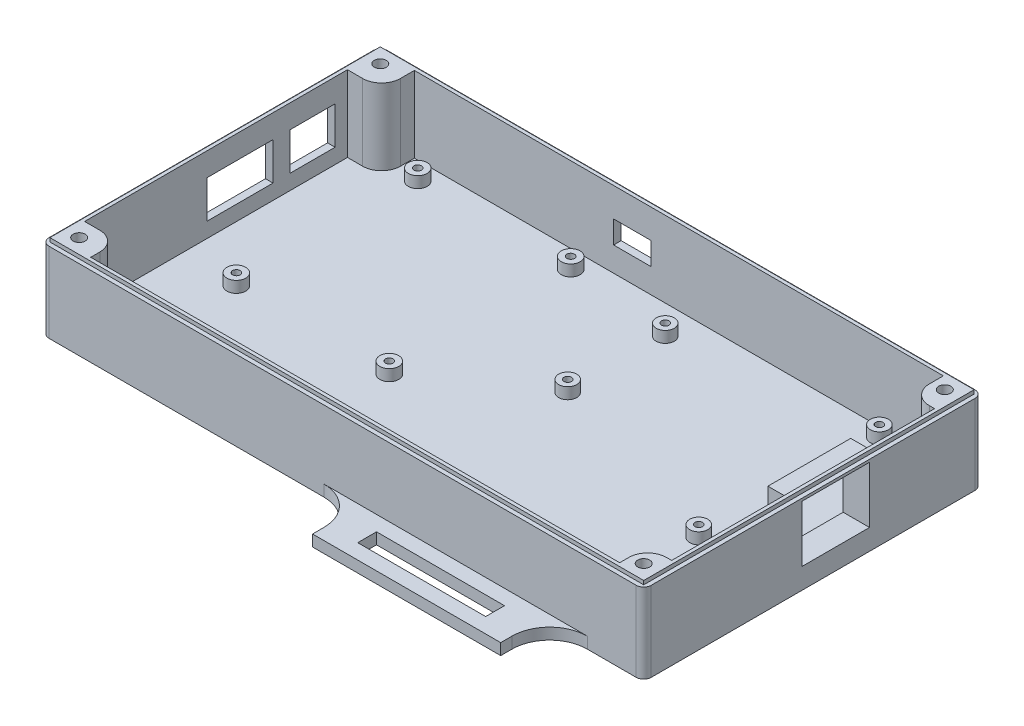
SolidWorks part; units mm, degrees
ref_plane "Front Plane" through (0, 0, 0) normal (0, 0, 1) x (1, 0, 0)
ref_plane "Top Plane" through (0, 0, 0) normal (0, 1, 0) x (1, 0, 0)
ref_plane "Right Plane" through (0, 0, 0) normal (1, 0, 0) x (0, 0, -1)
sketch "Sketch1" plane through (0, 0, 0) normal (0, 1, 0) x (1, 0, 0)
  line L1 (0, 0) -> (160, 0)
  line L2 (0, 0) -> (0, 90)
  line L3 (0, 90) -> (160, 90)
  line L4 (160, 0) -> (160, 90)
  dimension "D1" = 90
  dimension "D2" = 160
extrude "Boss-Extrude1" add sketch "Sketch1" along normal blind 22.2
shell "Shell1" thickness 2
sketch "Sketch2" plane through (0, 2, 0) normal (0, 1, 0) x (1, 0, 0)
  line L0 (2, 2) -> (158, 2) construction
  line L1 (158, 88) -> (2, 88) construction
  line L2 (2, 9.4298) -> (11.0517, 9.4298)
  line L3 (2, 9.4298) -> (2, 2)
  line L4 (2, 2) -> (158, 2) construction
  line L5 (2, 2) -> (11.0517, 2)
  line L6 (11.0517, 9.4298) -> (11.0517, 2)
  line L7 (2, 88) -> (2, 2) construction
  line L8 (151.6221, 79.2822) -> (158, 79.2822)
  line L9 (158, 88) -> (158, 79.2822)
  line L10 (151.6221, 2) -> (158, 2)
  line L11 (151.6221, 79.2822) -> (151.6221, 88)
  line L12 (158, 88) -> (151.6221, 88)
  line L13 (151.6221, 9.4298) -> (151.6221, 2)
  line L14 (158, 2) -> (158, 88) construction
  line L15 (151.6221, 9.4298) -> (158, 9.4298)
  line L16 (158, 9.4298) -> (158, 2)
  line L23 (2, 88) -> (11.0517, 88)
  line L24 (2, 88) -> (2, 79.2822)
  line L25 (2, 79.2822) -> (11.0517, 79.2822)
  line L26 (11.0517, 88) -> (11.0517, 79.2822)
  dimension "D1" = 6.3779
extrude "Boss-Extrude2" add sketch "Sketch2" along normal up to surface (20.2 mm away) up to face at (80, 22.2, -45)
sketch "Sketch5" plane through (0, 22.2, 0) normal (0, 1, 0) x (1, 0, 0)
  line L1 (160, 90) -> (0, 90)
  line L2 (160, 90) -> (160, 0)
  line L3 (160, 0) -> (0, 0)
  line L4 (0, 90) -> (0, 0)
  line L5 (1.1, 1.1) -> (158.9, 1.1)
  line L6 (1.1, 1.1) -> (1.1, 88.9)
  line L7 (1.1, 88.9) -> (158.9, 88.9)
  line L8 (158.9, 1.1) -> (158.9, 88.9)
  dimension "D1" = 1.1
  dimension "D2" = 1.1
  dimension "D3" = 1.1
  dimension "D4" = 1.1
extrude "Cut-Extrude2" cut sketch "Sketch5" against normal blind 1
sketch "Sketch6" plane through (0, 22.2, 0) normal (0, 1, 0) x (1, 0, 0)
  line L0 (160, 0) -> (160, 90) construction
  line L1 (0, 0) -> (160, 0) construction
  line L3 (160, 90) -> (0, 90) construction
  line L5 (0, 90) -> (0, 0) construction
  line L7 (0, 0) -> (160, 0) construction
  circle A0 centre (155, 85) radius 1.6
  circle A1 centre (155, 5) radius 1.6
  circle A2 centre (5, 85) radius 1.6
  circle A3 centre (5, 5) radius 1.6
  dimension "D8" = 3.2
  dimension "D9" = 5
  dimension "D1" = 5
  dimension "D2" = 5
  dimension "D3" = 5
  dimension "D4" = 5
  dimension "D5" = 5
  dimension "D6" = 5
  dimension "D7" = 5
extrude "Cut-Extrude3" cut sketch "Sketch6" against normal blind 25
sketch "Sketch13" plane through (0, 0, 0) normal (0, -1, 0) x (1, 0, 0)
  circle A0 centre (155, -5) radius 3
  circle A1 centre (155, -85) radius 3
  circle A2 centre (5, -5) radius 3
  circle A3 centre (5, -85) radius 3
  dimension "D1" = 6
extrude "Cut-Extrude8" cut sketch "Sketch13" against normal blind 15
sketch "Sketch14" plane through (0, 0, 0) normal (0, 0, 1) x (1, 0, 0)
  line L1 (135, 0) -> (85, 0)
  line L2 (135, 0) -> (135, 3)
  line L3 (135, 3) -> (85, 3)
  line L4 (85, 0) -> (85, 3)
  line L5 (160, 21.2) -> (160, 0) construction
  line L6 (0, 0) -> (160, 0) construction
  dimension "D1" = 0
  dimension "D2" = 3
  dimension "D3" = 50
  dimension "D4" = 25
extrude "Boss-Extrude4" add sketch "Sketch14" along normal blind 13
sketch "Sketch15" plane through (0, 0, 0) normal (0, -1, 0) x (-1, 0, 0)
  line L1 (-127, -4) -> (-93, -4)
  line L2 (-127, -4) -> (-127, -9)
  line L3 (-127, -9) -> (-93, -9)
  line L4 (-93, -4) -> (-93, -9)
  line L6 (-135, -13) -> (-85, -13) construction
  line L7 (-135, 0) -> (-85, 0) construction
  line L8 (-85, -13) -> (-85, 0) construction
  line L9 (-135, -13) -> (-135, 0) construction
  dimension "D1" = 8
  dimension "D2" = 8
  dimension "D3" = 4
  dimension "D4" = 4
extrude "Cut-Extrude9" cut sketch "Sketch15" against normal blind 10
sketch "Sketch16" plane through (0, 0, -90) normal (0, 0, -1) x (-1, 0, 0)
  line L1 (-135, 3) -> (-85, 3)
  line L2 (-135, 3) -> (-135, 0)
  line L3 (-135, 0) -> (-85, 0)
  line L4 (-85, 3) -> (-85, 0)
  line L5 (-160, 21.2) -> (-160, 0) construction
  line L6 (-160, 0) -> (0, 0) construction
  dimension "D1" = 3
  dimension "D2" = 0
  dimension "D3" = 25
  dimension "D4" = 50
extrude "Boss-Extrude5" add sketch "Sketch16" along normal blind 13
sketch "Sketch17" plane through (0, 0, 0) normal (0, -1, 0) x (-1, 0, 0)
  line L0 (-85, 90) -> (-135, 90) construction
  line L1 (-127, 99) -> (-93, 99)
  line L2 (-127, 99) -> (-127, 94)
  line L3 (-127, 94) -> (-93, 94)
  line L4 (-93, 99) -> (-93, 94)
  line L5 (-85, 103) -> (-135, 103) construction
  line L8 (-135, 103) -> (-135, 90) construction
  line L9 (-85, 103) -> (-85, 90) construction
  dimension "D1" = 4
  dimension "D2" = 4
  dimension "D3" = 8
  dimension "D4" = 8
extrude "Cut-Extrude10" cut sketch "Sketch17" against normal blind 10
sketch "Sketch22" plane through (0, 0, 0) normal (-1, 0, 0) x (0, 0, 1)
  line L0 (-90, 0) -> (0, 0) construction
  line L1 (-76, 16) -> (-64, 16)
  line L2 (-76, 16) -> (-76, 6)
  line L3 (-76, 6) -> (-64, 6)
  line L4 (-64, 16) -> (-64, 6)
  line L5 (-59.5, 6) -> (-42, 6)
  line L6 (-59.5, 6) -> (-59.5, 16)
  line L7 (-59.5, 16) -> (-42, 16)
  line L8 (-42, 6) -> (-42, 16)
  line L9 (-90, 21.2) -> (-90, 0) construction
  dimension "D1" = 17.5
  dimension "D2" = 4.5
  dimension "D3" = 10
  dimension "D4" = 6
  dimension "D5" = 10
  dimension "D6" = 12
  dimension "D7" = 6
  dimension "D8" = 14
extrude "Cut-Extrude15" cut sketch "Sketch22" against normal blind 10
sketch "Sketch23" plane through (0, 0, -90) normal (0, 0, -1) x (-1, 0, 0)
  line L1 (-74, 8.5) -> (-64, 8.5)
  line L2 (-74, 8.5) -> (-74, 14.5)
  line L3 (-74, 14.5) -> (-64, 14.5)
  line L4 (-64, 8.5) -> (-64, 14.5)
  line L5 (-160, 21.2) -> (-160, 0) construction
  line L6 (-160, 0) -> (-135, 0) construction
  dimension "D1" = 8.5
  dimension "D2" = 6
  dimension "D3" = 86
  dimension "D4" = 10
extrude "Cut-Extrude16" cut sketch "Sketch23" against normal blind 10
fillet "Fillet1" radius 10 4 edges at (135, 1.5, -90) (135, 1.5, 0) (85, 1.5, 0) (85, 1.5, -90)
fillet "Fillet4" radius 5 4 edges at (151.6221, 12.1, -79.2822) (151.6221, 12.1, -9.4298) (11.0517, 12.1, -9.4298) (11.0517, 12.1, -79.2822)
fillet "Fillet9" radius 2 4 edges at (0, 10.6, -90) (160, 10.6, -90) (160, 10.6, 0) (0, 10.6, 0)
sketch "Sketch26" plane through (0, 2, 0) normal (0, 1, 0) x (1, 0, 0)
  line L0 (151.6221, 88) -> (11.0517, 88) construction
  line L1 (2, 79.2822) -> (2, 9.4298) construction
  circle A0 centre (16.75, 83.2) radius 2.5
  circle A1 centre (16.75, 35) radius 2.5
  circle A2 centre (57.4, 35) radius 2.5
  circle A3 centre (57.4, 83.2) radius 2.5
  circle A4 centre (137.1221, 85.5) radius 2.4
  circle A5 centre (136.1221, 38.5) radius 2.4
  circle A6 centre (85.3221, 54.4784) radius 2.4
  circle A7 centre (85.3221, 80.4) radius 2.4
  dimension "D1" = 5
  dimension "D2" = 4.8
  dimension "D3" = 53
  dimension "D4" = 55.4
  dimension "D5" = 55.4
  dimension "D6" = 14.75
  dimension "D7" = 14.75
  dimension "D8" = 53
  dimension "D9" = 4.8
extrude "Boss-Extrude7" add sketch "Sketch26" along normal blind 3
sketch "Sketch27" plane through (0, 5, 0) normal (0, 1, 0) x (1, 0, 0)
  circle A0 centre (57.4, 83.2) radius 1
  circle A1 centre (57.4, 35) radius 1
  circle A2 centre (16.75, 35) radius 1
  circle A3 centre (16.75, 83.2) radius 1
  circle A4 centre (136.1221, 38.5) radius 1
  circle A5 centre (137.1221, 85.5) radius 1
  circle A6 centre (85.3221, 80.4) radius 1
  circle A7 centre (85.3221, 54.4784) radius 1
  dimension "D1" = 2
extrude "Cut-Extrude17" cut sketch "Sketch27" against normal blind 2
sketch "Sketch28" plane through (158, 0, 0) normal (-1, 0, 0) x (0, 0, 1)
  line L1 (-62, 21.5) -> (-40, 21.5)
  line L2 (-62, 21.5) -> (-62, 2)
  line L3 (-62, 2) -> (-40, 2)
  line L4 (-40, 21.5) -> (-40, 2)
  line L5 (-59, 20) -> (-59, 6.5) construction
  line L6 (-43, 20) -> (-59, 20) construction
  line L7 (-43, 6.5) -> (-43, 20) construction
  line L9 (-9.4298, 2) -> (-79.2822, 2) construction
  dimension "D1" = 3
  dimension "D2" = 1.5
  dimension "D3" = 3
extrude "Boss-Extrude8" add sketch "Sketch28" along normal blind 5
sketch "Sketch29" plane through (153, 0, 0) normal (-1, 0, 0) x (0, 0, 1)
  line L1 (-60, 20.5) -> (-42, 20.5)
  line L2 (-60, 20.5) -> (-60, 5.5)
  line L3 (-60, 5.5) -> (-42, 5.5)
  line L4 (-42, 20.5) -> (-42, 5.5)
  line L6 (-62, 21.5) -> (-62, 2) construction
  line L7 (-40, 21.5) -> (-62, 21.5) construction
  line L8 (-40, 2) -> (-40, 21.5) construction
  line L9 (-43, 6.5) -> (-59, 6.5) construction
  point P8 (-62, 11.75)
  dimension "D1" = 2
  dimension "D2" = 1
  dimension "D3" = 2
  dimension "D4" = 1
extrude "Cut-Extrude18" cut sketch "Sketch29" against normal blind 17
